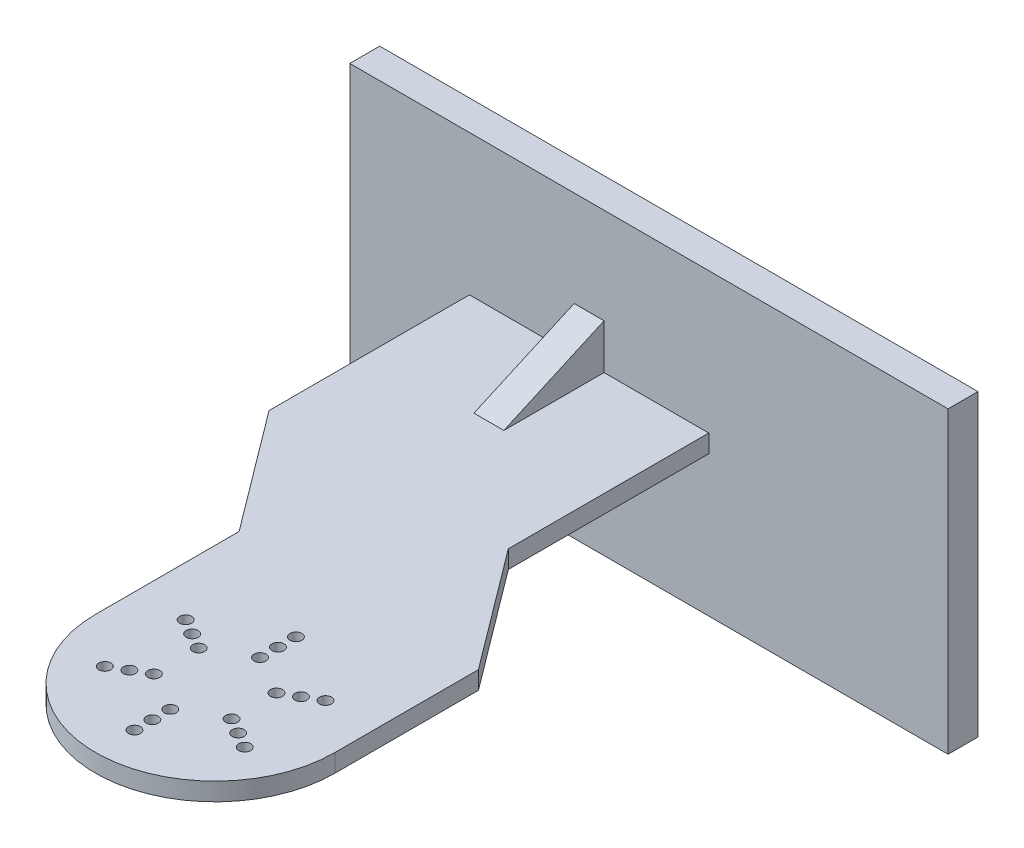
SolidWorks part; units mm, degrees
material "Polylactic Acid"
ref_plane "Top Plane" through (0, 0, 0) normal (0, 0, 1) x (1, 0, 0)
ref_plane "Right Plane" through (0, 0, 0) normal (0, 1, 0) x (1, 0, 0)
ref_plane "Front Plane" through (0, 0, 0) normal (1, 0, 0) x (0, 0, -1)
sketch "Sketch1" plane through (0, 0, 0) normal (0, 1, 0) x (1, 0, 0)
  line L1 (5, 77.5) -> (-35, 77.5)
  line L3 (0, 7.5) -> (0, 10.5) construction
  line L4 (0, 0) -> (0, 7.5) construction
  line L5 (20, 0) -> (20, 24)
  line L6 (20, 24) -> (5, 44)
  line L7 (5, 44) -> (5, 77.5)
  line L8 (-35, 77.5) -> (-35, 44)
  line L9 (-35, 44) -> (-20, 24)
  line L10 (-20, 24) -> (-20, 0)
  arc A0 (-20, 0) -> (20, 0) centre (0, 0) ccw
  circle A1 centre (0, 7.5) radius 1
  circle A2 centre (0, 10.5) radius 1
  circle A3 centre (0, 13.5) radius 1
  circle A4 centre (11.6913, 6.75) radius 1
  circle A5 centre (6.4952, 3.75) radius 1
  circle A6 centre (9.0933, 5.25) radius 1
  circle A7 centre (11.6913, -6.75) radius 1
  circle A8 centre (6.4952, -3.75) radius 1
  circle A9 centre (9.0933, -5.25) radius 1
  circle A10 centre (0, -13.5) radius 1
  circle A11 centre (0, -7.5) radius 1
  circle A12 centre (0, -10.5) radius 1
  circle A13 centre (-11.6913, -6.75) radius 1
  circle A14 centre (-6.4952, -3.75) radius 1
  circle A15 centre (-9.0933, -5.25) radius 1
  circle A16 centre (-11.6913, 6.75) radius 1
  circle A17 centre (-6.4952, 3.75) radius 1
  circle A18 centre (-9.0933, 5.25) radius 1
  point P0 (-15, 77.5)
  dimension "D1" = 20
  dimension "D5" = 2
  dimension "D2" = 77.5
  dimension "D4" = 3
  dimension "D7" = 7.5
  dimension "D9" = 15
  dimension "D10" = 20
  dimension "D11" = 24
  dimension "D8" = 40
  dimension "D3" = 3
  dimension "D6" = 6
extrude "Boss-Extrude1" add sketch "Sketch1" along normal mid plane 3
ref_plane "Plane1" through (-15, 0, 0) normal (1, 0, 0) x (0, 0, -1)
sketch "Sketch3" plane through (-15, 0, 0) normal (1, 0, 0) x (0, 0, -1)
  line L0 (60.75, 1.5) -> (77.5, 9)
  line L1 (44, 1.5) -> (77.5, 1.5) construction
  line L2 (77.5, 9) -> (77.5, 1.5)
  line L3 (77.5, 1.5) -> (60.75, 1.5)
  dimension "D1" = 7.5
extrude "Boss-Extrude2" add sketch "Sketch3" along normal mid plane 5
mirror "Mirror1" about plane through (0, 0, 0) normal (0, 1, 0) of "Boss-Extrude2"
sketch "Sketch4" plane through (-15, 0, 0) normal (1, 0, 0) x (0, 0, -1)
  line L1 (77.5, -25) -> (82.5, -25)
  line L2 (77.5, -25) -> (77.5, 25)
  line L3 (77.5, 25) -> (82.5, 25)
  line L4 (82.5, -25) -> (82.5, 25)
  point P4 (84.5777, -17.1337)
  point P6 (82.5, 0)
  dimension "D1" = 5
  dimension "D2" = 50
extrude "Boss-Extrude3" add sketch "Sketch4" along normal blind 60 and the other way blind 40
equation "\"D8@Sketch1\"=2*\"D1@Sketch1\""
